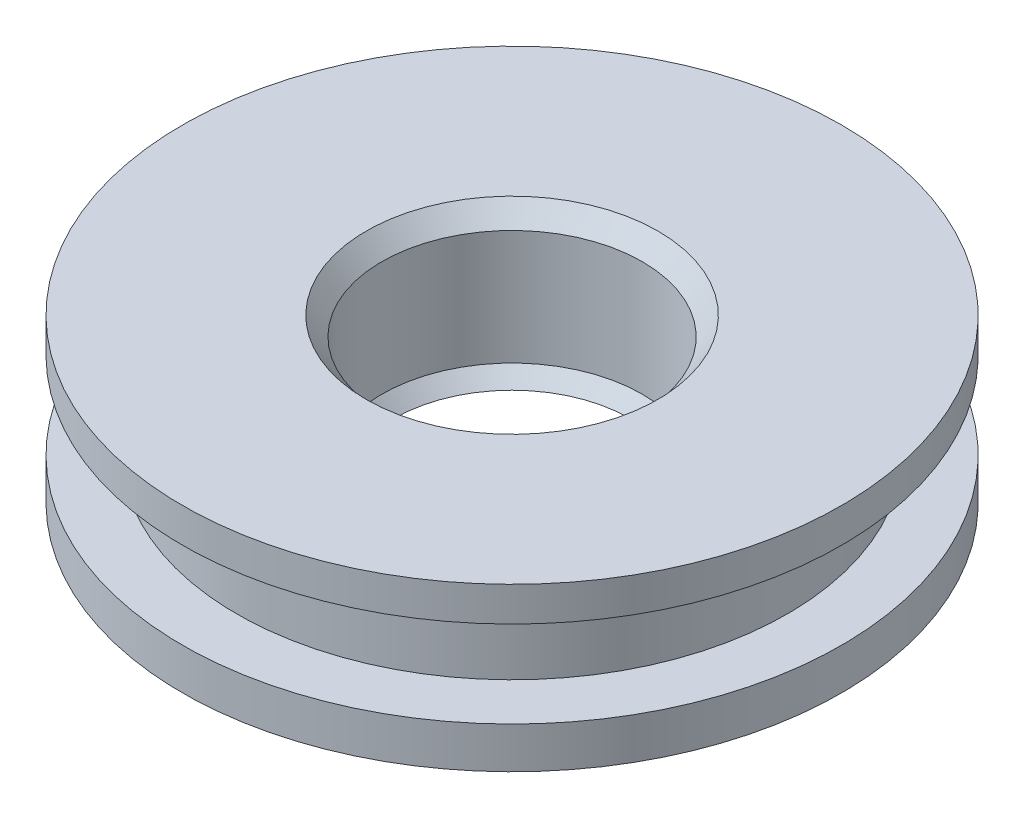
SolidWorks part; units mm, degrees
ref_plane "前视基准面" through (0, 0, 0) normal (0, 0, 1) x (1, 0, 0)
ref_plane "上视基准面" through (0, 0, 0) normal (0, 1, 0) x (1, 0, 0)
ref_plane "右视基准面" through (0, 0, 0) normal (1, 0, 0) x (0, 0, -1)
sketch "草图1" plane through (0, 0, 0) normal (0, 0, 1) x (1, 0, 0)
  line L0 (0.8228, 0.0964) -> (1.4353, 0.0964)
  line L1 (1.4353, 0.0964) -> (1.4353, 0.2764)
  line L2 (1.4353, 0.2764) -> (1.1992, 0.2764)
  line L3 (1.1992, 0.2764) -> (1.1992, 0.6534)
  line L4 (1.1992, 0.6534) -> (1.4353, 0.6534)
  line L7 (0.5671, 0.7222) -> (0.5671, 0.2222)
  line L8 (0.5671, 0.2222) -> (0.5131, 0.1578)
  line L11 (0, -1.5732) -> (0, 1.5732) construction
  line L20 (0.5131, 0.1578) -> (0.6708, 0.1578)
  line L21 (0.6353, 0.8034) -> (1.4353, 0.8034)
  line L23 (1.4353, 0.8034) -> (1.4353, 0.6534)
  line L24 (0.3103, 0.0164) -> (1.6676, 0.0164) construction
  line L25 (0.6708, 0.1578) -> (0.8228, 0.0964)
  line L26 (0.6353, 0.8034) -> (0.5671, 0.7222)
  point P2 (0.5401, 0.19)
  point P15 (0, 0)
  dimension "D1" = 0.08
  dimension "D2" = 40
  dimension "D3" = 0.18
  dimension "D4" = 0.15
  dimension "D5" = 0.8
  dimension "D6" = 68
revolve "旋转1" add sketch "草图1" angle 360 about L11
